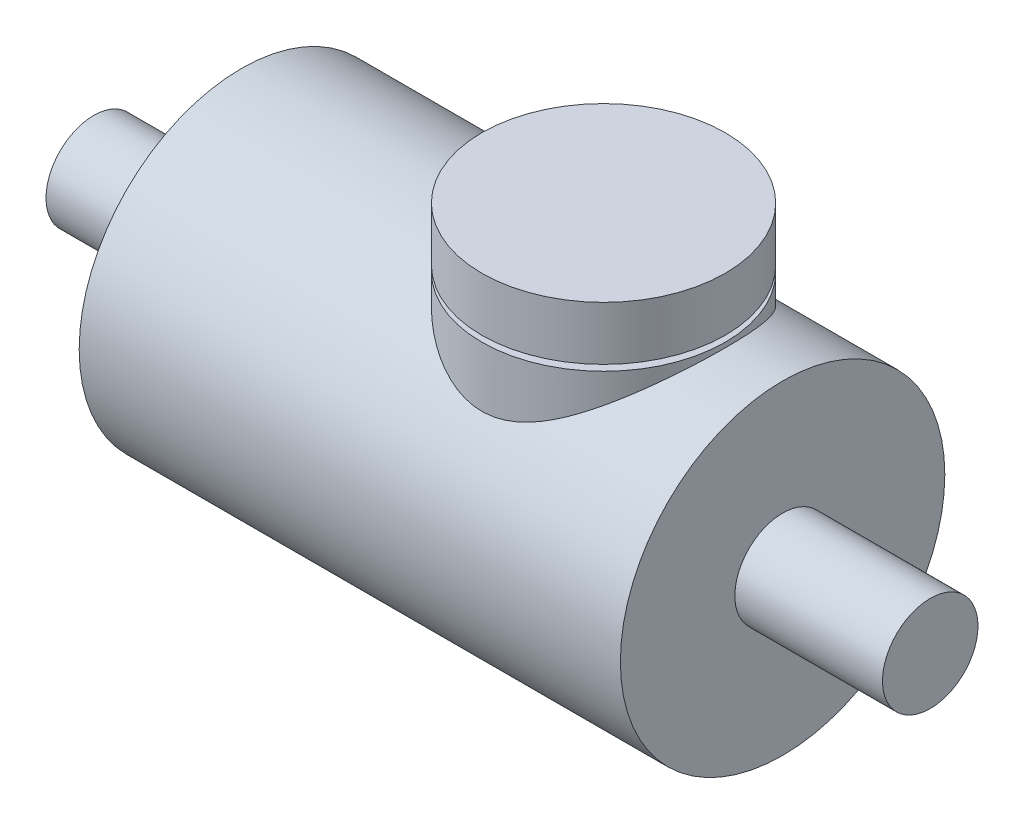
SolidWorks part; units mm, degrees
ref_plane "Alzado" through (0, 0, 0) normal (0, 0, 1) x (1, 0, 0)
ref_plane "Planta" through (0, 0, 0) normal (0, 1, 0) x (1, 0, 0)
ref_plane "Vista lateral" through (0, 0, 0) normal (1, 0, 0) x (0, 0, -1)
sketch "Croquis1" plane through (0, 0, 0) normal (1, 0, 0) x (0, 0, -1)
  circle A0 centre (0, 0) radius 13.59
  dimension "D1" = 27.18
extrude "Saliente-Extruir1" add sketch "Croquis1" along normal blind 45.34
sketch "Croquis2" plane through (45.34, 0, 0) normal (1, 0, 0) x (0, 0, -1)
  circle A0 centre (0, 0) radius 4
  dimension "D1" = 8
extrude "Saliente-Extruir2" add sketch "Croquis2" along normal blind 12.37
sketch "Croquis3" plane through (0, 0, 0) normal (-1, 0, 0) x (0, 0, 1)
  circle A0 centre (0, 0) radius 4
  dimension "D1" = 8
extrude "Saliente-Extruir3" add sketch "Croquis3" along normal blind 12.37
sketch "Croquis4" plane through (0, 0, 0) normal (0, 1, 0) x (1, 0, 0)
  line L0 (-12.37, 0) -> (57.71, 0) construction
  line L1 (-12.37, 4) -> (-12.37, -4) construction
  line L2 (57.71, -4) -> (57.71, 4) construction
  line L3 (45.34, -13.59) -> (45.34, 13.59) construction
  circle A0 centre (30.34, 0) radius 10.2
  dimension "D1" = 20.4
  dimension "D2" = 15
extrude "Saliente-Extruir4" add sketch "Croquis4" along normal blind 14
sketch "Croquis5" plane through (0, 14, 0) normal (0, 1, 0) x (1, 0, 0)
  circle A0 centre (30.34, 0) radius 9.4408
extrude "Saliente-Extruir5" add sketch "Croquis5" along normal blind 0.5
sketch "Croquis6" plane through (0, 14.5, 0) normal (0, 1, 0) x (1, 0, 0)
  circle A0 centre (30.34, 0) radius 10.2
extrude "Saliente-Extruir6" add sketch "Croquis6" along normal blind 4.5
